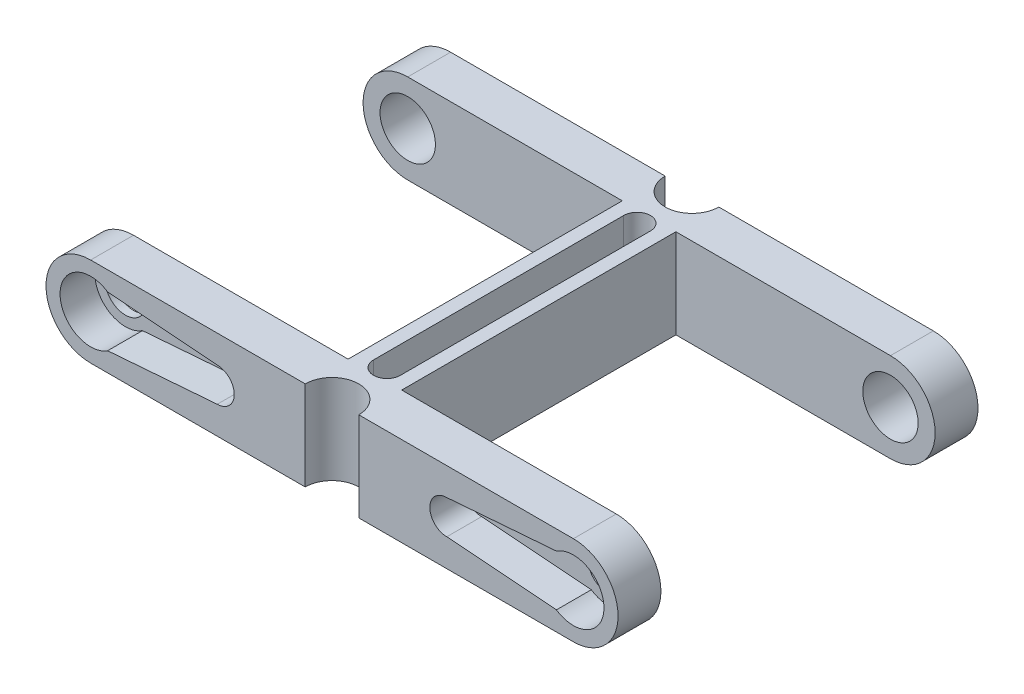
SolidWorks part; units mm, degrees
ref_plane "Front Plane" through (0, 0, 0) normal (0, 0, 1) x (1, 0, 0)
ref_plane "Top Plane" through (0, 0, 0) normal (0, 1, 0) x (1, 0, 0)
ref_plane "Right Plane" through (0, 0, 0) normal (1, 0, 0) x (0, 0, -1)
sketch "Sketch1" plane through (0, 0, 0) normal (0, 0, 1) x (1, 0, 0)
  line L0 (-27.0233, 0) -> (27.0233, 0) construction
  line L1 (-27.0233, 5) -> (27.0233, 5)
  line L2 (-27.0233, -5) -> (27.0233, -5)
  arc A0 (-27.0233, 5) -> (-27.0233, -5) centre (-27.0233, 0) ccw
  arc A1 (27.0233, -5) -> (27.0233, 5) centre (27.0233, 0) ccw
  point P2 (0, 0)
  point P8 (32.0233, 0)
  dimension "D1" = 5
  dimension "D2" = 54.0465
extrude "Boss-Extrude1" add sketch "Sketch1" along normal mid plane 40.3
sketch "Sketch2" plane through (0, 5, 0) normal (0, 1, 0) x (1, 0, 0)
  line L0 (0, 0) -> (0, 20.15) construction
  line L1 (0, 0) -> (7.8559, 0) construction
  line L2 (0, -14) -> (0, 14) construction
  line L3 (-1.5, -14) -> (-1.5, 14)
  line L4 (27.0233, 20.15) -> (-27.0233, 20.15) construction
  line L12 (1.5, -14) -> (1.5, 14)
  line L13 (27.0233, 15.35) -> (38.0583, 15.35)
  line L14 (27.0233, -15.35) -> (38.0583, -15.35)
  line L15 (38.0583, -15.35) -> (38.0583, 15.35)
  line L16 (-27.0233, -15.35) -> (-38.0583, -15.35)
  line L17 (-27.0233, 15.35) -> (-38.0583, 15.35)
  line L18 (-38.0583, -15.35) -> (-38.0583, 15.35)
  line L19 (-27.0233, 15.35) -> (-3, 15.35)
  line L20 (-3, 15.35) -> (-3, -15.35)
  line L21 (-3, -15.35) -> (-27.0233, -15.35)
  line L22 (3, -15.35) -> (27.0233, -15.35)
  line L23 (3, 15.35) -> (3, -15.35)
  line L24 (27.0233, 15.35) -> (3, 15.35)
  arc A0 (-1.5, -14) -> (1.5, -14) centre (0, -14) ccw
  arc A1 (1.5, 14) -> (-1.5, 14) centre (0, 14) ccw
  circle A2 centre (0, 20.15) radius 3
  circle A3 centre (0, -20.15) radius 3
  point P10 (0, 0)
  dimension "D3" = 6
  dimension "D2" = 28
  dimension "D5" = 3
  dimension "D6" = 3
  dimension "D1" = 4.8
extrude "Cut-Extrude1" cut sketch "Sketch2" against normal through all both and the other way through all
sketch "Sketch4" plane through (0, 0, 20.15) normal (0, 0, 1) x (1, 0, 0)
  line L0 (-27.0233, 0) -> (27.0233, 0) construction
  line L1 (-27.0233, 0) -> (27.0233, 0) construction
  line L2 (25.1237, 2.85) -> (12.8483, 1.9)
  line L3 (12.8483, -1.9) -> (25.1237, -2.85)
  line L4 (0, 0) -> (0, 10.0499) construction
  line L5 (-25.1237, 2.85) -> (-12.8483, 1.9)
  line L6 (-12.8483, -1.9) -> (-25.1237, -2.85)
  arc A0 (25.1237, -2.85) -> (25.1237, 2.85) centre (27.0233, 0) ccw
  arc A1 (12.8483, 1.9) -> (12.8483, -1.9) centre (12.8483, 0) ccw
  arc A2 (-12.8483, 1.9) -> (-12.8483, -1.9) centre (-12.8483, 0) cw
  arc A3 (-25.1237, -2.85) -> (-25.1237, 2.85) centre (-27.0233, 0) cw
  circle A4 centre (-27.0233, 0) radius 2.3 construction
  circle A5 centre (27.0233, 0) radius 2.3 construction
  point P3 (12.8483, 0)
  point P6 (25.1237, 2.85)
  point P7 (25.1237, -2.85)
  dimension "D1" = 6.85
  dimension "D3" = 3.8
  dimension "D5" = 4.6
  dimension "D2" = 14.175
  dimension "D4" = 5.7
extrude "Cut-Extrude2" cut sketch "Sketch4" against normal blind 3.9
sketch "Sketch5" plane through (0, 0, 0) normal (0, 0, 1) x (1, 0, 0)
  circle A0 centre (27.0233, 0) radius 2.3 construction
  circle A1 centre (-27.0233, 0) radius 2.3 construction
  circle A2 centre (27.0233, 0) radius 2.3
  circle A3 centre (-27.0233, 0) radius 2.3
extrude "Cut-Extrude4" cut sketch "Sketch5" along normal up to surface (16.25 mm away) up to face at (-19.8421, 0, 16.25)
sketch "Sketch7" plane through (0, 0, 0) normal (0, 0, 1) x (1, 0, 0)
  line L0 (0, 0) -> (0, 10.0499) construction
  line L1 (-27.0233, 0) -> (27.0233, 0) construction
  line L2 (0, 0) -> (0, 10.0499) construction
  line L3 (-27.0233, 0) -> (27.0233, 0) construction
  circle A0 centre (27.0233, 0) radius 3.1
  circle A1 centre (-27.0233, 0) radius 3.1
  dimension "D1" = 6.2
extrude "Cut-Extrude5" cut sketch "Sketch7" against normal through all from surface at -15.35 starting at face at (16.2616, 0, -15.35)
